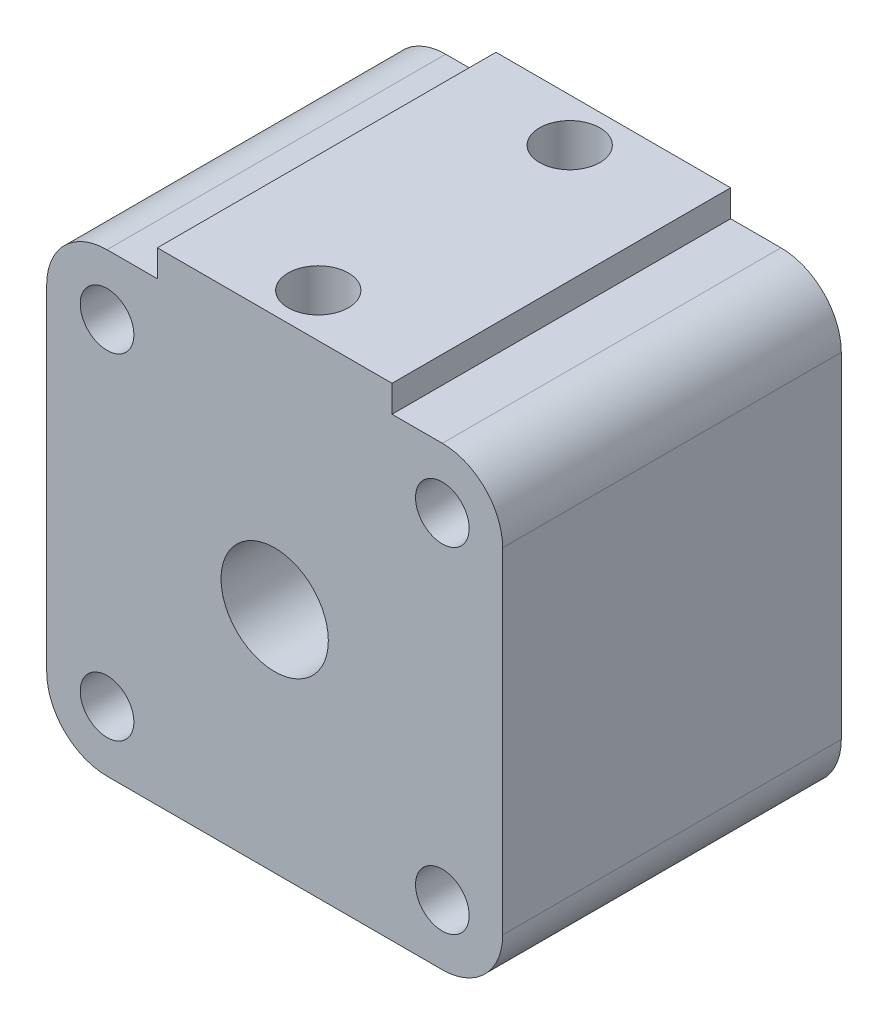
SolidWorks part; units mm, degrees
ref_plane "Alzado" through (0, 0, 0) normal (0, 0, 1) x (1, 0, 0)
ref_plane "Planta" through (0, 0, 0) normal (0, 1, 0) x (1, 0, 0)
ref_plane "Vista lateral" through (0, 0, 0) normal (1, 0, 0) x (0, 0, -1)
sketch "Croquis1" plane through (0, 0, 0) normal (0, 0, 1) x (1, 0, 0)
  line L0 (-17.5, 34) -> (-17.5, 38)
  line L1 (-25, 34) -> (-17.5, 34)
  line L2 (-34, 25) -> (-34, -25)
  line L3 (-25, -34) -> (25, -34)
  line L4 (34, 25) -> (34, -25)
  line L5 (-34, 34) -> (34, -34) construction
  line L6 (-34, -34) -> (34, 34) construction
  line L7 (-17.5, 38) -> (17.5, 38)
  line L8 (17.5, 38) -> (17.5, 34)
  line L9 (17.5, 34) -> (25, 34)
  arc A0 (25, 34) -> (34, 25) centre (25, 25) cw
  arc A1 (34, -25) -> (25, -34) centre (25, -25) cw
  arc A2 (-25, -34) -> (-34, -25) centre (-25, -25) cw
  arc A3 (-34, 25) -> (-25, 34) centre (-25, 25) cw
  point P0 (0, 0)
  dimension "D3" = 9
  dimension "D1" = 68
  dimension "D2" = 68
  dimension "D4" = 4
  dimension "D5" = 17.5
  dimension "D6" = 17.5
extrude "Saliente-Extruir1" add sketch "Croquis1" against normal blind 50.5
sketch "Croquis2" plane through (0, 0, 0) normal (0, 0, 1) x (1, 0, 0)
  circle A0 centre (-25, 25) radius 4
  circle A1 centre (-25, -25) radius 4
  circle A2 centre (25, -25) radius 4
  circle A3 centre (25, 25) radius 4
  dimension "D1" = 8
  dimension "D2" = 8
  dimension "D3" = 8
  dimension "D4" = 8
extrude "Cortar-Extruir1" cut sketch "Croquis2" against normal blind 20
sketch "Croquis3" plane through (0, 0, 0) normal (0, 0, 1) x (1, 0, 0)
  circle A0 centre (0, 0) radius 8
  dimension "D1" = 16
extrude "Cortar-Extruir2" cut sketch "Croquis3" against normal blind 20
sketch "Croquis4" plane through (0, 38, 0) normal (0, 1, 0) x (1, 0, 0)
  line L0 (17.5, 0) -> (-17.5, 0) construction
  line L1 (17.5, 50.5) -> (-17.5, 50.5) construction
  circle A0 centre (0, 6.5) radius 4.5
  circle A1 centre (0, 44) radius 4.5
  dimension "D1" = 9
  dimension "D2" = 9
  dimension "D3" = 6.5
  dimension "D4" = 6.5
extrude "Cortar-Extruir3" cut sketch "Croquis4" against normal blind 10
